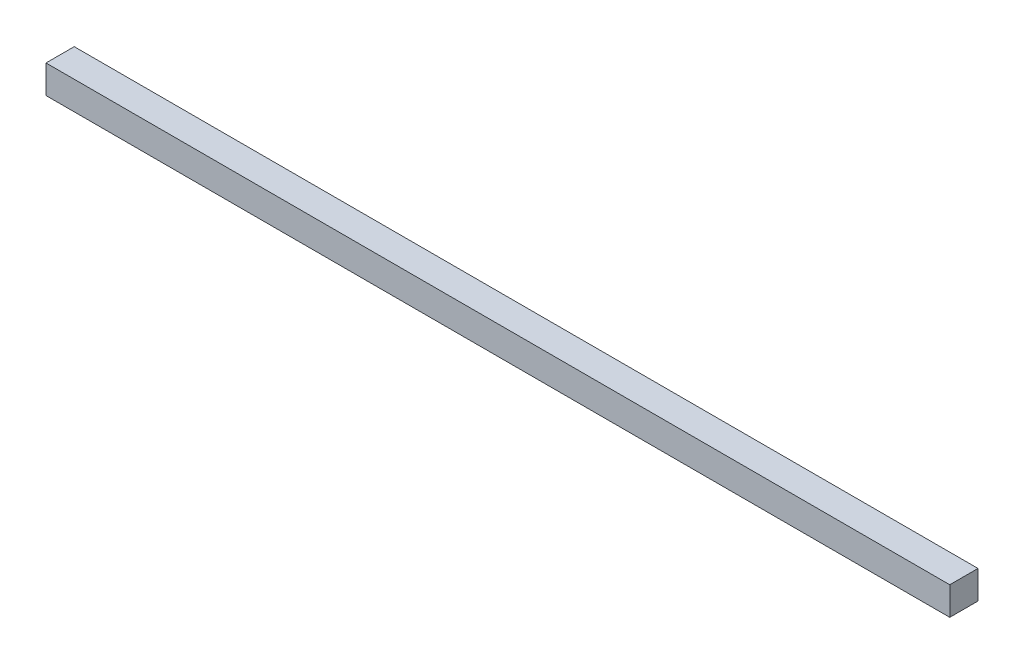
SolidWorks part; units mm, degrees
ref_plane "Front Plane" through (0, 0, 0) normal (0, 0, 1) x (1, 0, 0)
ref_plane "Top Plane" through (0, 0, 0) normal (0, 1, 0) x (1, 0, 0)
ref_plane "Right Plane" through (0, 0, 0) normal (1, 0, 0) x (0, 0, -1)
sketch "Sketch1" plane through (0, 0, 0) normal (0, 1, 0) x (1, 0, 0)
  line L1 (0, 0) -> (1219.2, 0)
  line L2 (0, 0) -> (0, 38.1)
  line L3 (0, 38.1) -> (1219.2, 38.1)
  line L4 (1219.2, 0) -> (1219.2, 38.1)
  dimension "D1" = 1219.2
  dimension "D2" = 38.1
extrude "Extrude1" add sketch "Sketch1" along normal blind 38.1
